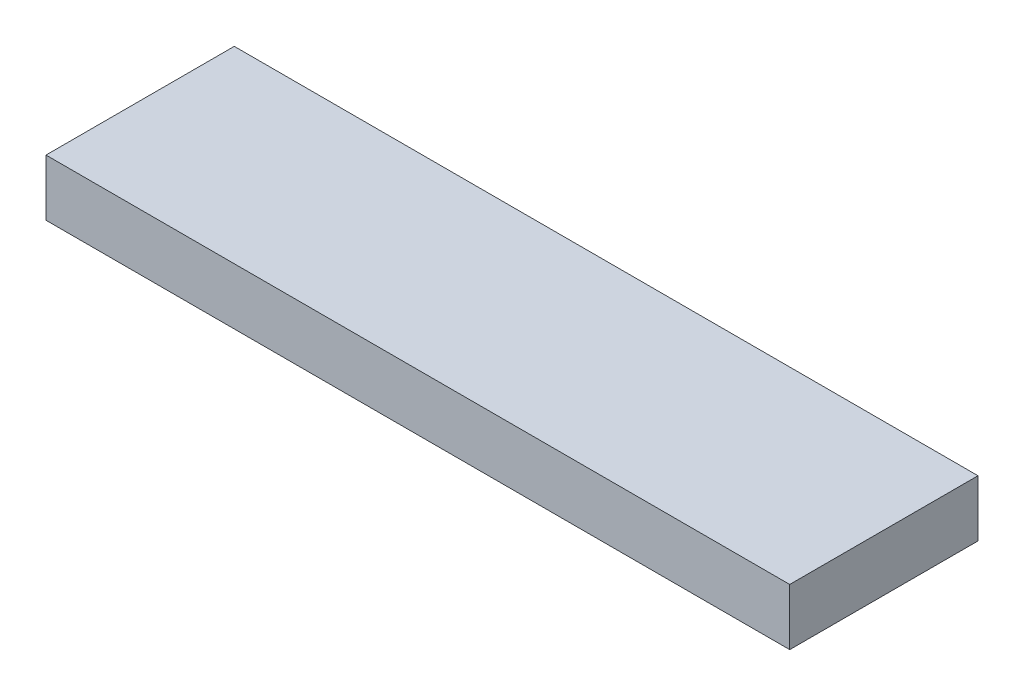
SolidWorks part; units mm, degrees
ref_plane "Front Plane" through (0, 0, 0) normal (0, 0, 1) x (1, 0, 0)
ref_plane "Top Plane" through (0, 0, 0) normal (0, 1, 0) x (1, 0, 0)
ref_plane "Right Plane" through (0, 0, 0) normal (1, 0, 0) x (0, 0, -1)
sketch "Sketch1" plane through (0, 0, 0) normal (0, 1, 0) x (1, 0, 0)
  line L1 (-1351.8204, 642.3544) -> (2598.1796, 642.3544)
  line L2 (-1351.8204, 642.3544) -> (-1351.8204, -357.6456)
  line L3 (-1351.8204, -357.6456) -> (2598.1796, -357.6456)
  line L4 (2598.1796, 642.3544) -> (2598.1796, -357.6456)
  dimension "D1" = 3950
  dimension "D2" = 1000
extrude "Boss-Extrude1" add sketch "Sketch1" along normal blind 300
